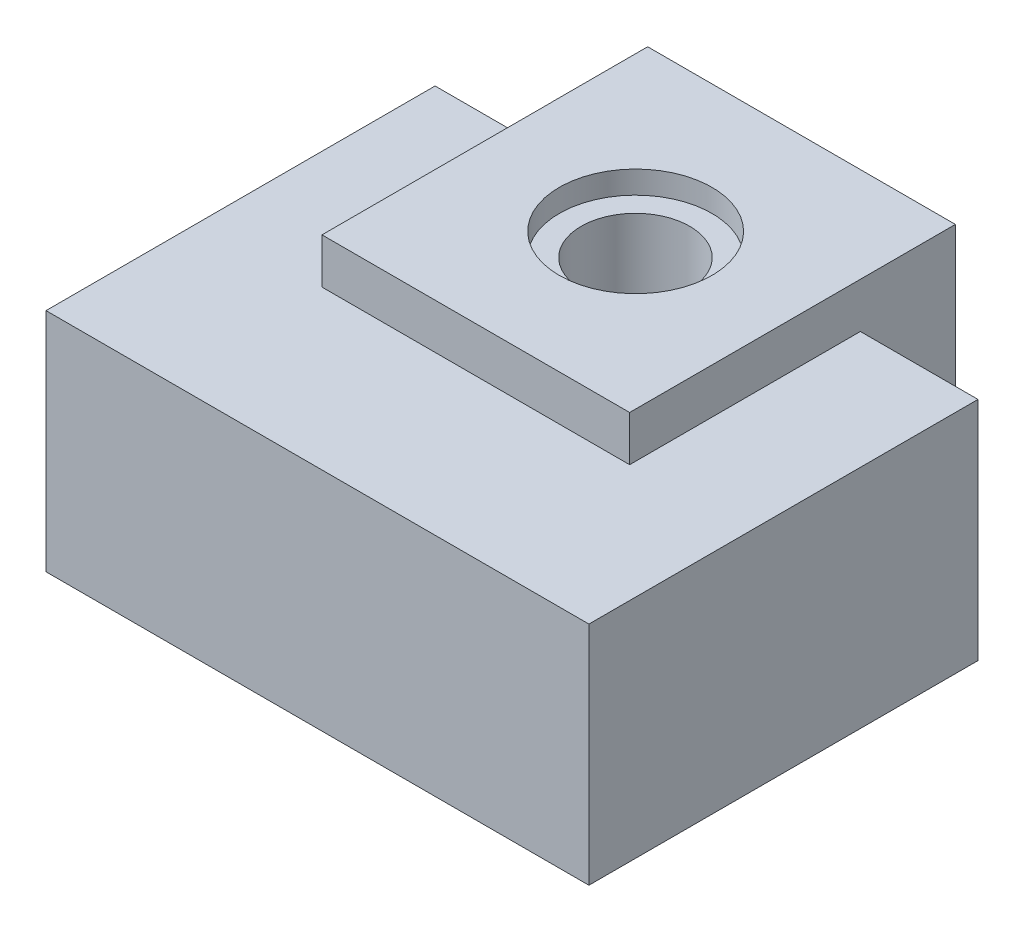
SolidWorks part; units mm, degrees
material "Chrome Stainless Steel"
ref_plane "Front Plane" through (0, 0, 0) normal (0, 0, 1) x (1, 0, 0)
ref_plane "Top Plane" through (0, 0, 0) normal (0, 1, 0) x (1, 0, 0)
ref_plane "Right Plane" through (0, 0, 0) normal (1, 0, 0) x (0, 0, -1)
sketch "Sketch1" plane through (0, 0, 0) normal (0, 1, 0) x (1, 0, 0)
  line L1 (0, 0) -> (60, 0)
  line L2 (0, 0) -> (0, 43)
  line L3 (0, 43) -> (60, 43)
  line L4 (60, 0) -> (60, 43)
  dimension "D1" = 60
  dimension "D2" = 43
extrude "Boss-Extrude1" add sketch "Sketch1" along normal blind 25
sketch "Sketch2" plane through (0, 25, 0) normal (0, 1, 0) x (1, 0, 0)
  line L0 (30, 0) -> (30, 43) construction
  line L1 (0, 0) -> (60, 0) construction
  line L2 (60, 43) -> (0, 43) construction
  line L3 (0, 8.5) -> (60, 8.5) construction
  line L4 (0, 43) -> (0, 0) construction
  line L5 (60, 0) -> (60, 43) construction
  line L7 (13, 43) -> (47, 43)
  line L8 (13, 43) -> (13, 17.5)
  line L9 (13, 17.5) -> (47, 17.5)
  line L10 (47, 43) -> (47, 17.5)
  dimension "D1" = 8.5
  dimension "D2" = 34
  dimension "D3" = 17
  dimension "D4" = 25.5
extrude "Boss-Extrude2" add sketch "Sketch2" along normal blind 5
sketch "Sketch5" plane through (0, 0, -43) normal (0, 0, -1) x (-1, 0, 0)
  line L1 (-47, 30) -> (-12.9927, 30)
  line L2 (-47, 30) -> (-47, 0)
  line L3 (-47, 0) -> (-12.9927, 0)
  line L4 (-12.9927, 30) -> (-12.9927, 0)
  dimension "D1" = 30
extrude "Boss-Extrude3" add sketch "Sketch5" along normal blind 10.5
sketch "Sketch6" plane through (0, 30, 0) normal (0, 1, 0) x (1, 0, 0)
  line L0 (29.9964, 53.5) -> (30, 17.5) construction
  line L1 (12.9927, 53.5) -> (47, 53.5) construction
  line L2 (13, 17.5) -> (47, 17.5) construction
  line L3 (47, 35.5) -> (13, 35.5) construction
  line L4 (47, 17.5) -> (47, 53.5) construction
  line L5 (13, 43) -> (13, 17.5) construction
  circle A0 centre (29.9982, 35.1447) radius 6
  dimension "D1" = 12
extrude "Cut-Extrude1" cut sketch "Sketch6" against normal through all
sketch "Sketch7" plane through (0, 30, 0) normal (0, 1, 0) x (1, 0, 0)
  line L0 (29.9964, 53.5) -> (30, 17.5) construction
  line L1 (12.9927, 53.5) -> (47, 53.5) construction
  line L2 (13, 17.5) -> (47, 17.5) construction
  circle A0 centre (29.9982, 35.1659) radius 5.9788
  circle A1 centre (29.9982, 35.1659) radius 8.4376
extrude "Cut-Extrude2" cut sketch "Sketch7" against normal mid plane 5 contours A1 | A0
